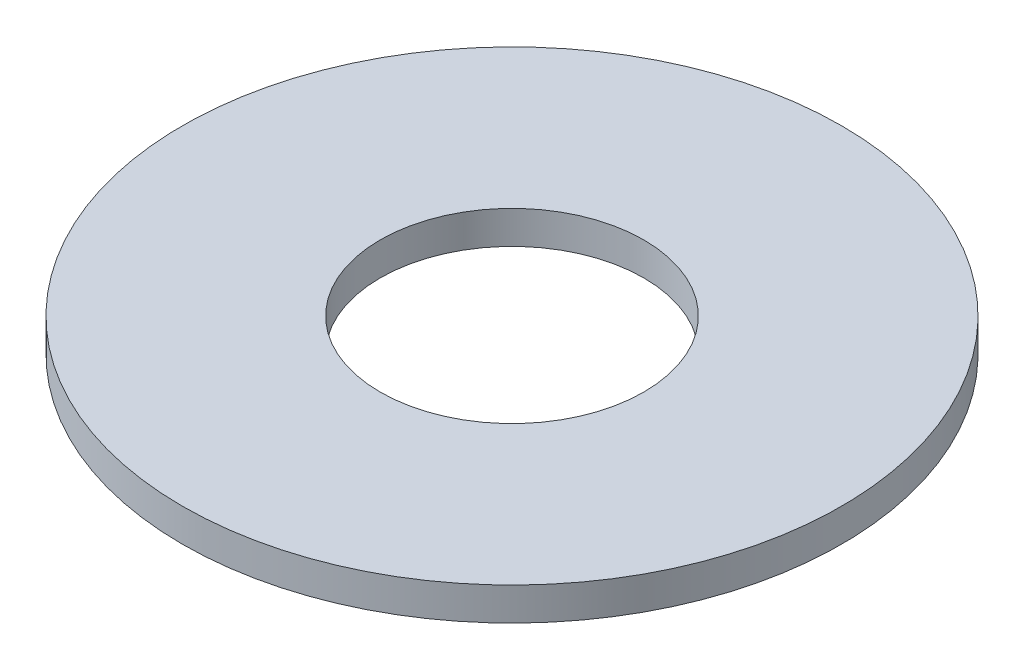
SolidWorks part; units mm, degrees
material "AISI 304"
ref_plane "前视基准面" through (0, 0, 0) normal (0, 0, 1) x (1, 0, 0)
ref_plane "上视基准面" through (0, 0, 0) normal (0, 1, 0) x (1, 0, 0)
ref_plane "右视基准面" through (0, 0, 0) normal (1, 0, 0) x (0, 0, -1)
other "Configuration Table"
sketch "草图1" plane through (0, 0, 0) normal (0, 1, 0) x (1, 0, 0)
  circle A0 centre (0, 0) radius 5
  circle A1 centre (0, 0) radius 2
  dimension "D1" = 4
  dimension "D2" = 10
extrude "凸台-拉伸1" add sketch "草图1" along normal blind 0.5
